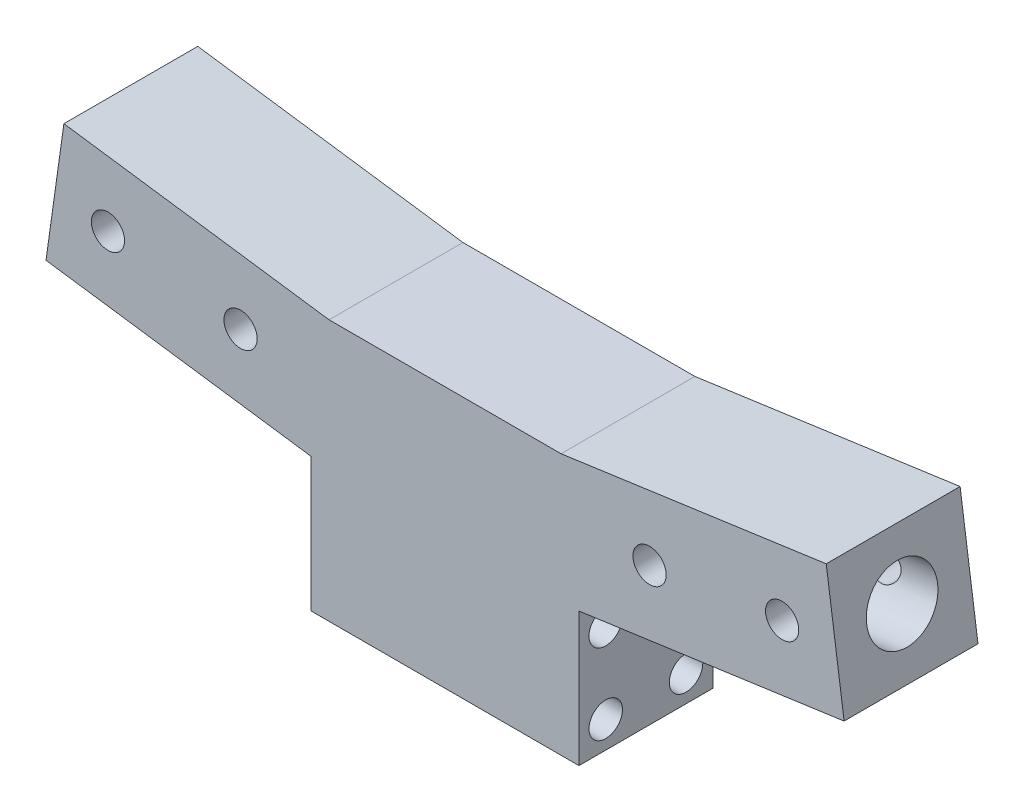
SolidWorks part; units mm, degrees
ref_plane "Front Plane" through (0, 0, 0) normal (0, 0, 1) x (1, 0, 0)
ref_plane "Top Plane" through (0, 0, 0) normal (0, 1, 0) x (1, 0, 0)
ref_plane "Right Plane" through (0, 0, 0) normal (1, 0, 0) x (0, 0, -1)
sketch "Sketch1" plane through (0, 0, 0) normal (0, 0, 1) x (1, 0, 0)
  line L1 (-25, -12.5) -> (25, -12.5)
  line L2 (-25, -12.5) -> (-25, 12.5)
  line L3 (-25, 12.5) -> (25, 12.5)
  line L4 (25, -12.5) -> (25, 12.5)
  line L5 (-25, -12.5) -> (25, 12.5) construction
  line L6 (-25, 12.5) -> (25, -12.5) construction
  point P0 (0, 0)
  dimension "D1" = 50
  dimension "D2" = 25
extrude "Boss-Extrude1" add sketch "Sketch1" along normal blind 25
sketch "Sketch3" plane through (0, 0, 25) normal (0, 0, 1) x (1, 0, 0)
  line L0 (-25, 12.5) -> (-74.5134, 19.4587)
  line L2 (-25, 12.5) -> (-58.6977, 12.5) construction
  line L3 (-21.6598, 36.2664) -> (-71.1732, 43.2251)
  line L4 (-71.1732, 43.2251) -> (-74.5134, 19.4587)
  line L5 (-21.6598, 36.2664) -> (21.6598, 36.2664)
  line L6 (0, 36.2664) -> (0, 12.5) construction
  line L7 (25, 12.5) -> (-25, 12.5) construction
  line L8 (-25, 12.5) -> (-21.6598, 36.2664) construction
  line L9 (-25, 12.5) -> (25, 12.5)
  line L10 (25, 12.5) -> (21.6598, 36.2664) construction
  line L11 (71.1732, 43.2251) -> (74.5134, 19.4587)
  line L12 (21.6598, 36.2664) -> (71.1732, 43.2251)
  line L13 (25, 12.5) -> (58.6977, 12.5) construction
  line L14 (25, 12.5) -> (74.5134, 19.4587)
  dimension "D1" = 8
  dimension "D3" = 50
  dimension "D2" = 24
extrude "Boss-Extrude2" add sketch "Sketch3" against normal up to surface (25 mm away) up to face at (0, 0, 0)
sketch "Sketch4" plane through (-75.7519, 10.6462, 0) normal (-0.9903, 0.1392, 0) x (0, 0, 1)
  line L0 (0, 20.899) -> (25, 20.899) construction
  line L1 (0, 32.899) -> (0, 8.899) construction
  line L2 (25, 32.899) -> (25, 8.899) construction
  circle A0 centre (12.5, 20.899) radius 6.625
  dimension "D1" = 13.25
extrude "Cut-Extrude1" cut sketch "Sketch4" against normal blind 50
mirror "Mirror1" about plane through (0, 0, 0) normal (1, 0, 0) of "Cut-Extrude1"
sketch "Sketch5" plane through (0, 0, 25) normal (0, 0, 1) x (1, 0, 0)
  line L0 (-72.8433, 31.3419) -> (0, 21.1044) construction
  line L1 (-71.1732, 43.2251) -> (-74.5134, 19.4587) construction
  line L2 (0, 36.2664) -> (0, -12.5) construction
  line L3 (21.6598, 36.2664) -> (-21.6598, 36.2664) construction
  line L4 (-25, -12.5) -> (25, -12.5) construction
  line L5 (-74.5134, 19.4587) -> (-25, 12.5) construction
  line L6 (72.8433, 31.3419) -> (0, 21.1044) construction
  circle A0 centre (-62.9406, 29.9501) radius 3.1
  circle A1 centre (-38.1839, 26.4708) radius 3.1
  circle A2 centre (38.1839, 26.4708) radius 3.1
  circle A3 centre (62.9406, 29.9501) radius 3.1
  dimension "D1" = 6.2
  dimension "D3" = 6.2
  dimension "D2" = 10
  dimension "D4" = 25
extrude "Cut-Extrude2" cut sketch "Sketch5" against normal through all
sketch "Sketch6" plane through (25, 0, 0) normal (1, 0, 0) x (0, 0, -1)
  line L0 (-25, 12.5) -> (-20, 12.5) construction
  line L1 (-25, 12.5) -> (0, 12.5) construction
  line L2 (-20, 12.5) -> (-20, 7.5) construction
  line L3 (0, -12.5) -> (0, 12.5) construction
  line L4 (-25, -12.5) -> (0, -12.5) construction
  circle A0 centre (-20, 7.5) radius 3.125
  circle A1 centre (-5, 7.5) radius 3.125
  circle A2 centre (-5, -7.5) radius 3.125
  circle A3 centre (-20, -7.5) radius 3.125
  dimension "D3" = 6.25
  dimension "D1" = 5
  dimension "D2" = 5
  dimension "D6" = 5
  dimension "D7" = 5
  dimension "D8" = 5
  dimension "D4" = 2
  dimension "D5" = 2
extrude "Cut-Extrude3" cut sketch "Sketch6" against normal through all
